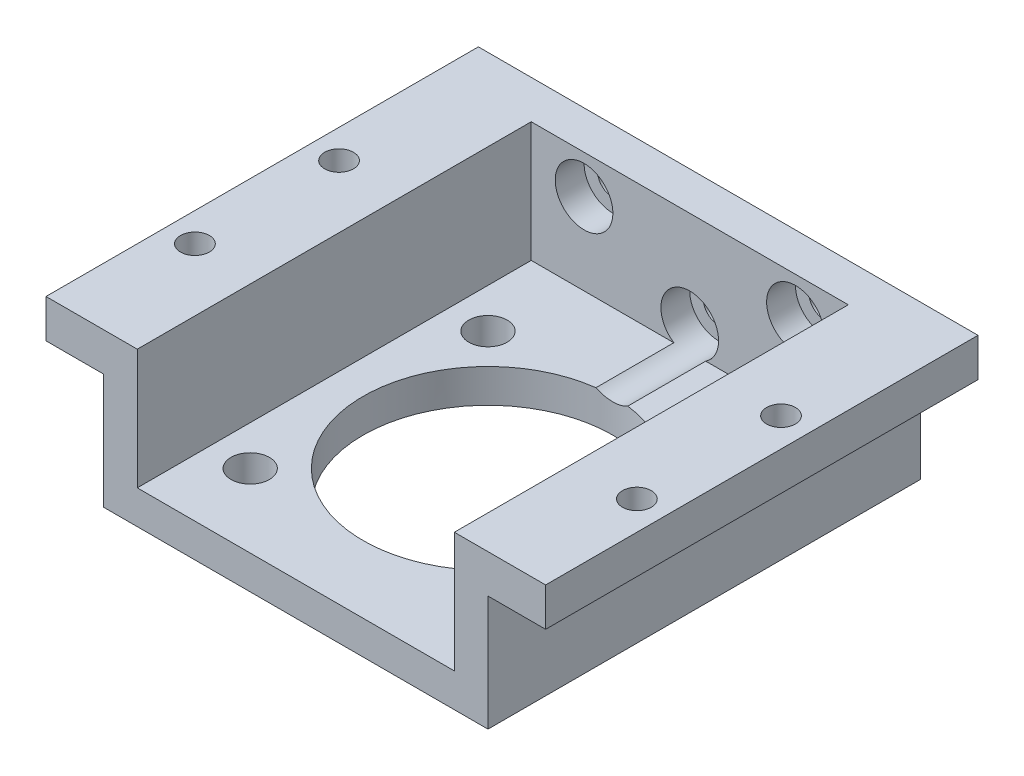
SolidWorks part; units mm, degrees
material "6061 合金"
ref_plane "前视基准面" through (0, 0, 0) normal (0, 0, 1) x (1, 0, 0)
ref_plane "上视基准面" through (0, 0, 0) normal (0, 1, 0) x (1, 0, 0)
ref_plane "右视基准面" through (0, 0, 0) normal (1, 0, 0) x (0, 0, -1)
sketch "草图1" plane through (0, 0, 0) normal (0, 0, 1) x (1, 0, 0)
  line L0 (0, 0) -> (0, 41.1065) construction
  line L1 (-16.5, 27.3988) -> (-16.5, 16.3988)
  line L2 (-26, 27.3988) -> (-16.5, 27.3988)
  line L3 (-26, 27.3988) -> (-26, 21.3988)
  line L4 (-20, 11.3988) -> (20, 11.3988)
  line L5 (26, 27.3988) -> (26, 21.3988)
  line L6 (-26, 21.3988) -> (-20, 21.3988)
  line L7 (16.5, 27.3988) -> (26, 27.3988)
  line L9 (-20, 21.3988) -> (-20, 11.3988)
  line L10 (20, 16.3988) -> (20, 11.3988)
  line L11 (20, 16.3988) -> (20, 21.3988)
  line L12 (20, 21.3988) -> (26, 21.3988)
  line L13 (-16.5, 16.3988) -> (16.5, 16.3988)
  line L14 (16.5, 16.3988) -> (16.5, 27.3988)
  dimension "D1" = 52
  dimension "D2" = 6
  dimension "D3" = 6
  dimension "D4" = 5
  dimension "D5" = 3.5
  dimension "D6" = 9.5
  dimension "D7" = 11
extrude "凸台-拉伸1" add sketch "草图1" along normal blind 40
sketch "草图2" plane through (0, 11.3988, 0) normal (0, -1, 0) x (1, 0, 0)
  line L1 (-20, 20) -> (20, 20) construction
  line L2 (-20, 40) -> (-20, 0) construction
  line L3 (20, 40) -> (20, 0) construction
  circle A0 centre (0, 20) radius 13
  dimension "D1" = 26
extrude "切除-拉伸1" cut sketch "草图2" against normal blind 1.5
sketch "草图3" plane through (0, 12.8988, 0) normal (0, -1, 0) x (1, 0, 0)
  circle A0 centre (0, 20) radius 13
  dimension "D1" = 26
extrude "切除-拉伸2" cut sketch "草图3" against normal through all
sketch "草图4" plane through (0, 11.3988, 0) normal (0, -1, 0) x (1, 0, 0)
  line L0 (0, 20) -> (0, 33.6149) construction
  line L1 (0, 20) -> (13.7279, 33.7279) construction
  circle A0 centre (12.3744, 32.3744) radius 2
  dimension "D2" = 4
  dimension "D3" = 17.5
  dimension "D1" = 45
extrude "切除-拉伸3" cut sketch "草图4" against normal up to next
pattern_circular "阵列(圆周)1" count 4 over 360 about axis through (0, 0, 20) along (0, 1, 0) of "切除-拉伸3"
sketch "草图5" plane through (0, 21.3988, 0) normal (0, -1, 0) x (1, 0, 0)
  line L0 (-26, 20) -> (-20, 20) construction
  line L1 (-26, 40) -> (-26, 0) construction
  line L2 (-20, 40) -> (-20, 0) construction
  line L3 (-23, 40) -> (-23, 0) construction
  line L4 (-26, 40) -> (-20, 40) construction
  line L5 (-26, 0) -> (-20, 0) construction
  circle A0 centre (-23, 27.5) radius 1.5
  circle A1 centre (-23, 12.5) radius 1.5
  dimension "D1" = 3
  dimension "D3" = 15
  dimension "D4" = 7.5
extrude "切除-拉伸4" cut sketch "草图5" against normal through all
ref_plane "基准面1" through (0, 0, 0) normal (-1, 0, 0) x (0, 0, 1)
mirror "镜向1" about plane through (0, 0, 0) normal (-1, 0, 0) of "切除-拉伸4"
sketch "草图6" plane through (0, 16.3988, 0) normal (0, 1, 0) x (1, 0, 0)
  line L4 (16.5, 0) -> (-16.5, 0)
  line L5 (-16.5, 0) -> (-16.5, -40)
  line L6 (-16.5, -40) -> (16.5, -40)
  line L7 (16.5, -40) -> (16.5, 0)
  line L8 (16.5, 0) -> (-16.5, 0)
  line L9 (-16.5, 0) -> (-16.5, -40)
  line L10 (-16.5, -40) -> (16.5, -40)
  line L11 (16.5, -40) -> (16.5, 0)
  dimension "D1" = 0
extrude "切除-拉伸5" cut sketch "草图6" against normal blind 1.5
sketch "草图7" plane through (0, 21.3988, 0) normal (0, -1, 0) x (1, 0, 0)
  line L0 (-26, 0) -> (-20, 0) construction
  line L1 (-20, 0) -> (-20, 40) construction
  line L2 (-20, 40) -> (-26, 40) construction
  line L3 (-26, 40) -> (-26, 0) construction
  line L4 (20, 0) -> (26, 0) construction
  line L5 (26, 0) -> (26, 40) construction
  line L6 (26, 40) -> (20, 40) construction
  line L7 (20, 40) -> (20, 0) construction
  line L8 (-26, 0) -> (-20, 0)
  line L9 (-20, 0) -> (-20, 40)
  line L10 (-20, 40) -> (-26, 40)
  line L11 (-26, 40) -> (-26, 0)
  line L12 (20, 0) -> (26, 0)
  line L13 (26, 0) -> (26, 40)
  line L14 (26, 40) -> (20, 40)
  line L15 (20, 40) -> (20, 0)
extrude "切除-拉伸6" cut sketch "草图7" against normal blind 2
sketch "草图8" plane through (0, 0, 0) normal (0, 0, 1) x (1, 0, 0)
  line L12 (20, 11.3988) -> (20, 23.3988)
  line L13 (20, 23.3988) -> (26, 23.3988)
  line L14 (26, 23.3988) -> (26, 27.3988)
  line L15 (26, 27.3988) -> (16.5, 27.3988)
  line L16 (16.5, 27.3988) -> (16.5, 14.8988)
  line L17 (16.5, 14.8988) -> (-16.5, 14.8988)
  line L18 (-16.5, 14.8988) -> (-16.5, 27.3988)
  line L19 (-16.5, 27.3988) -> (-26, 27.3988)
  line L20 (-26, 27.3988) -> (-26, 23.3988)
  line L21 (-26, 23.3988) -> (-20, 23.3988)
  line L22 (-20, 23.3988) -> (-20, 11.3988)
  line L23 (-20, 11.3988) -> (20, 11.3988)
  line L24 (20, 11.3988) -> (20, 23.3988)
  line L25 (20, 23.3988) -> (26, 23.3988)
  line L26 (26, 23.3988) -> (26, 27.3988)
  line L27 (26, 27.3988) -> (16.5, 27.3988)
  line L28 (16.5, 27.3988) -> (16.5, 14.8988)
  line L29 (16.5, 14.8988) -> (-16.5, 14.8988)
  line L30 (-16.5, 14.8988) -> (-16.5, 27.3988)
  line L31 (-16.5, 27.3988) -> (-26, 27.3988)
  line L32 (-26, 27.3988) -> (-26, 23.3988)
  line L33 (-26, 23.3988) -> (-20, 23.3988)
  line L34 (-20, 23.3988) -> (-20, 11.3988)
  line L35 (-20, 11.3988) -> (20, 11.3988)
  dimension "D1" = 0
extrude "凸台-拉伸2" add sketch "草图8" against normal blind 5
sketch "草图9" plane through (0, 14.8988, 0) normal (0, 1, 0) x (1, 0, 0)
  line L0 (16.5, -40) -> (16.5, 5) construction
  line L1 (-16.5, 5) -> (16.5, 5)
  line L2 (-16.5, 5) -> (-16.5, 1)
  line L3 (-16.5, 1) -> (16.5, 1)
  line L4 (16.5, 5) -> (16.5, 1)
  dimension "D1" = 4
extrude "凸台-拉伸3" add sketch "草图9" along normal up to surface (12.5 mm away) up to face at (-23, 27.3988, 11)
sketch "草图10" plane through (0, 0, -5) normal (0, 0, -1) x (-1, 0, 0)
  line L0 (0, -972.6012) -> (0, 49027.3988) construction
  line L1 (-1020, 17.3988) -> (48980, 17.3988) construction
  line L8 (-20, 11.3988) -> (20, 11.3988)
  line L9 (20, 11.3988) -> (20, 23.3988)
  line L10 (20, 23.3988) -> (26, 23.3988)
  line L11 (26, 23.3988) -> (26, 27.3988)
  line L12 (26, 27.3988) -> (-26, 27.3988)
  line L13 (-26, 27.3988) -> (-26, 23.3988)
  line L14 (-26, 23.3988) -> (-20, 23.3988)
  line L15 (-20, 23.3988) -> (-20, 11.3988)
  line L16 (-20, 11.3988) -> (20, 11.3988)
  line L17 (20, 11.3988) -> (20, 23.3988)
  line L18 (20, 23.3988) -> (26, 23.3988)
  line L19 (26, 23.3988) -> (26, 27.3988)
  line L20 (26, 27.3988) -> (-26, 27.3988)
  line L21 (-26, 27.3988) -> (-26, 23.3988)
  line L22 (-26, 23.3988) -> (-20, 23.3988)
  line L23 (-20, 23.3988) -> (-20, 11.3988)
  circle A0 centre (0, 17.3988) radius 1.6
  circle A1 centre (-11, 23.3988) radius 1.6
  circle A2 centre (11, 23.3988) radius 1.6
  point P11 (0, 27.3988)
  point P14 (-20, 17.3988)
  dimension "D2" = 3.2
  dimension "D3" = 3.2
  dimension "D4" = 11
  dimension "D5" = 6
  dimension "D1" = 0
extrude "切除-拉伸7" cut sketch "草图10" against normal blind 4 contours A1 | A0 | A2
sketch "草图11" plane through (0, 0, -1) normal (0, 0, 1) x (1, 0, 0)
  circle A1 centre (-11, 23.3988) radius 1.6 construction
  circle A2 centre (-11, 23.3988) radius 1.6
  circle A3 centre (11, 23.3988) radius 1.6 construction
  circle A4 centre (11, 23.3988) radius 1.6
  circle A5 centre (0, 17.3988) radius 1.6 construction
  circle A6 centre (0, 17.3988) radius 1.6
  circle A7 centre (-11, 23.3988) radius 3
  circle A8 centre (0, 17.3988) radius 3
  circle A9 centre (11, 23.3988) radius 3
  dimension "D1" = 6
  dimension "D2" = 6
  dimension "D3" = 6
  dimension "D4" = 22
extrude "切除-拉伸8" cut sketch "草图11" against normal blind 3
sketch "草图12" plane through (0, 0, -1) normal (0, 0, 1) x (1, 0, 0)
  arc A0 (1.6583, 14.8988) -> (-1.6583, 14.8988) centre (0, 17.3988) ccw construction
  circle A1 centre (0, 17.3988) radius 3
extrude "切除-拉伸9" cut sketch "草图12" along normal blind 14
